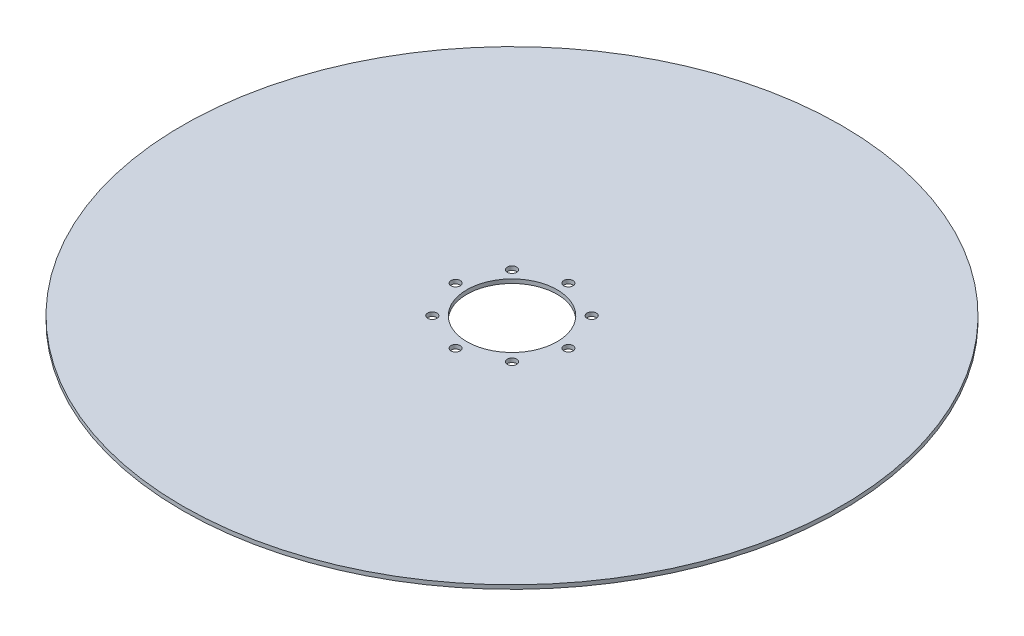
SolidWorks part; units mm, degrees
ref_plane "Front Plane" through (0, 0, 0) normal (0, 0, 1) x (1, 0, 0)
ref_plane "Top Plane" through (0, 0, 0) normal (0, 1, 0) x (1, 0, 0)
ref_plane "Right Plane" through (0, 0, 0) normal (1, 0, 0) x (0, 0, -1)
sketch "Sketch1" plane through (0, 0, 0) normal (0, 1, 0) x (1, 0, 0)
  line L0 (0, 0) -> (-15.026, 15.026) construction
  line L1 (0, -29.7405) -> (0, 30.4631) construction
  line L2 (-15.026, -15.026) -> (0, 0) construction
  circle A0 centre (0, 0) radius 124.25
  circle A1 centre (0, 0) radius 17
  circle A2 centre (0, 0) radius 21.25 construction
  circle A3 centre (0, -21.25) radius 1.75
  circle A4 centre (-15.026, -15.026) radius 1.75
  circle A5 centre (-21.25, 0) radius 1.75
  circle A6 centre (-15.026, 15.026) radius 1.75
  circle A7 centre (0, 21.25) radius 1.75
  circle A8 centre (15.026, 15.026) radius 1.75
  circle A9 centre (21.25, 0) radius 1.75
  circle A10 centre (15.026, -15.026) radius 1.75
  dimension "D1" = 248.5
  dimension "D2" = 34
  dimension "D3" = 3.5
  dimension "D6" = 42.5
  dimension "D4" = 45
  dimension "D5" = 90
extrude "а" add sketch "Sketch1" along normal mid plane 1.5
